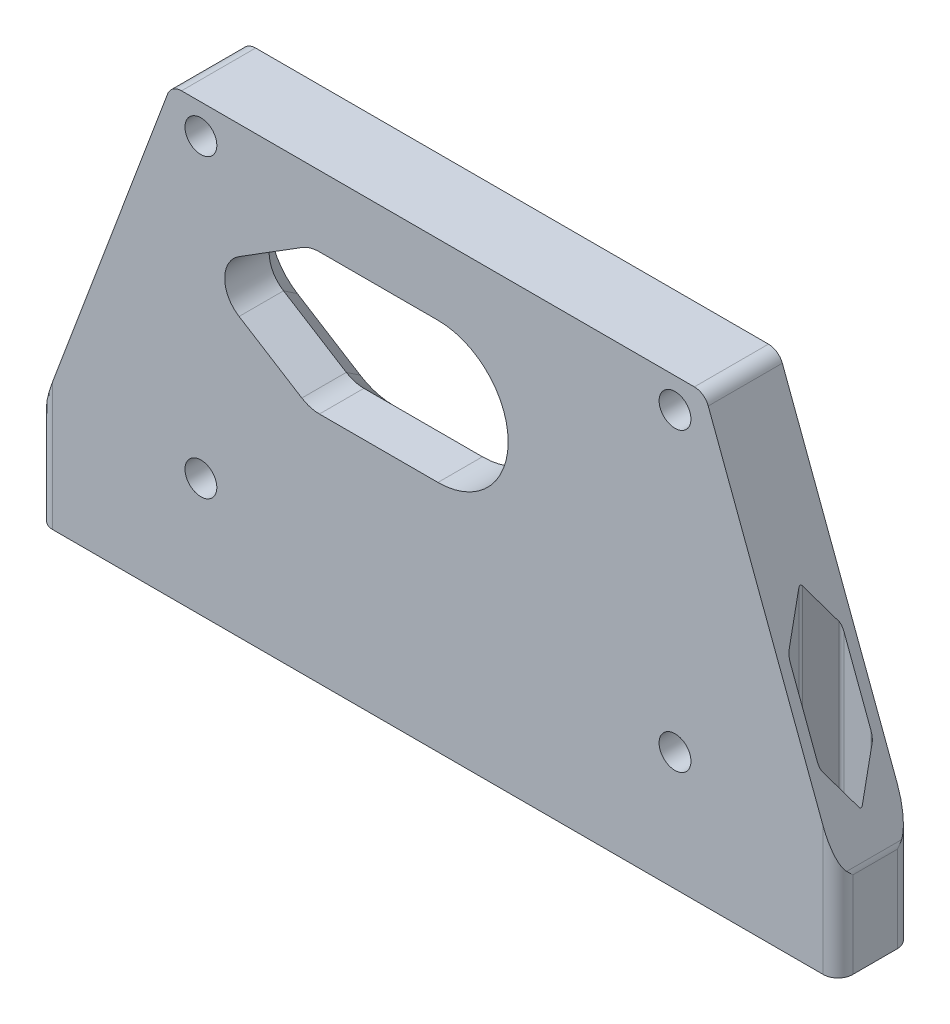
SolidWorks part; units mm, degrees
material "ABS"
ref_plane "前视基准面" through (0, 0, 0) normal (0, 0, 1) x (1, 0, 0)
ref_plane "上视基准面" through (0, 0, 0) normal (0, 1, 0) x (1, 0, 0)
ref_plane "右视基准面" through (0, 0, 0) normal (1, 0, 0) x (0, 0, -1)
other "Configuration Table"
sketch "草图1" plane through (0, 0, 0) normal (0, 0, 1) x (1, 0, 0)
  line L0 (-54, 0) -> (54, 0)
  line L1 (-54, 0) -> (-54, 12)
  line L2 (-54, 12) -> (-36, 60)
  line L3 (-36, 60) -> (36, 60)
  line L4 (36, 60) -> (54, 12)
  line L5 (54, 12) -> (54, 0)
  line L6 (0, 60) -> (0, 0) construction
  line L8 (32, 16) -> (-32, 16) construction
  line L9 (32, 16) -> (32, 56) construction
  line L10 (32, 56) -> (-32, 56) construction
  line L11 (-32, 16) -> (-32, 56) construction
  line L12 (32, 16) -> (-32, 56) construction
  line L13 (32, 56) -> (-32, 16) construction
  circle A0 centre (-32, 56) radius 2.15
  circle A1 centre (32, 56) radius 2.15
  circle A2 centre (32, 16) radius 2.15
  circle A3 centre (-32, 16) radius 2.15
  point P4 (0, 0)
  point P11 (0, 36)
  dimension "D6" = 4.3
  dimension "D1" = 72
  dimension "D2" = 48
  dimension "D3" = 12
  dimension "D4" = 18
  dimension "D5" = 24
  dimension "D7" = 64
  dimension "D8" = 40
extrude "凸台-拉伸1" add sketch "草图1" along normal blind 10
sketch "草图2" plane through (0, 0, 0) normal (0, -1, 0) x (1, 0, 0)
  line L0 (36, 0) -> (-36, 0) construction
  line L1 (0, 5) -> (0, 0) construction
  circle A0 centre (0, 5) radius 2.15 construction
  circle A1 centre (8, 5) radius 2.15 construction
  circle A2 centre (16, 5) radius 2.15 construction
  circle A3 centre (24, 5) radius 2.15 construction
  circle A4 centre (32, 5) radius 2.15 construction
  circle A5 centre (40, 5) radius 2.15 construction
  circle A6 centre (48, 5) radius 2.15
  circle A7 centre (-48, 5) radius 2.15
  dimension "D1" = 5
  dimension "D2" = 4.3
  dimension "D3" = 7
extrude "切除-拉伸1" cut sketch "草图2" against normal through all
sketch "草图3" plane through (0, 60, 0) normal (0, 1, 0) x (1, 0, 0)
  line L1 (-43.8142, -5) -> (-45.9071, -1.375)
  line L2 (-45.9071, -1.375) -> (-50.0929, -1.375)
  line L3 (-50.0929, -1.375) -> (-52.1858, -5)
  line L4 (-52.1858, -5) -> (-50.0929, -8.625)
  line L5 (-50.0929, -8.625) -> (-45.9071, -8.625)
  line L6 (-45.9071, -8.625) -> (-43.8142, -5)
  line L7 (43.8142, -5) -> (45.9071, -8.625)
  line L8 (45.9071, -8.625) -> (50.0929, -8.625)
  line L9 (50.0929, -8.625) -> (52.1858, -5)
  line L10 (52.1858, -5) -> (50.0929, -1.375)
  line L11 (50.0929, -1.375) -> (45.9071, -1.375)
  line L12 (45.9071, -1.375) -> (43.8142, -5)
  circle A0 centre (-48, -5) radius 3.625 construction
  circle A1 centre (48, -5) radius 3.625 construction
  dimension "D1" = 7.25
  dimension "D2" = 7.25
extrude "切除-拉伸2" cut sketch "草图3" against normal offset from surface (50 mm away) 10 up to face at (-48, 0, 7.15)
fillet "圆角1" radius 0.5 12 edges at (50.0929, 16.2095, 1.375) (52.1858, 13.4189, 5) (50.0929, 16.2095, 8.625) (45.9071, 21.7905, 8.625) (43.8142, 24.5811, 5) (45.9071, 21.7905, 1.375) (-45.9071, 21.7905, 8.625) (-50.0929, 16.2095, 8.625) (-52.1858, 13.4189, 5) (-50.0929, 16.2095, 1.375) (-43.8142, 24.5811, 5) (-45.9071, 21.7905, 1.375)
fillet "圆角2" radius 2 8 edges at (54, 6, 0) (54, 6, 10) (-54, 6, 0) (-54, 6, 10) (-54, 12, 5) (54, 12, 5) (36, 60, 5) (-36, 60, 5)
sketch "草图4" plane through (0, 0, 0) normal (0, 0, -1) x (-1, 0, 0)
  line L0 (18.374, 49.7975) -> (26.8482, 44.4999)
  line L1 (18.374, 32.2025) -> (26.8482, 37.5001)
  line L2 (0, 50.4785) -> (16, 50.4785)
  line L3 (0, 31.5215) -> (16, 31.5215)
  circle A1 centre (0, 41) radius 9.4785
  circle A5 centre (24.6603, 41) radius 4.1275
  circle A6 centre (16, 36) radius 3.8185 construction
  circle A7 centre (16, 46) radius 3.8185 construction
  circle A8 centre (16, 46) radius 4.4785
  circle A9 centre (16, 36) radius 4.4785
extrude "切除-拉伸3" cut sketch "草图4" against normal through all contours A1 | A9 L1 A5 L0 A8 L2 A1 L3 | A8 | A9 | A5
chamfer "倒角1" distance 4 angle 45 8 edges at (-22.6111, 34.8513, 0) (-17.2349, 31.6951, 0) (-28.7878, 41, 0) (-8, 31.5215, 0) (-22.6111, 47.1487, 0) (9.4785, 41, 0) (-17.2349, 50.3049, 0) (-8, 50.4785, 0)
